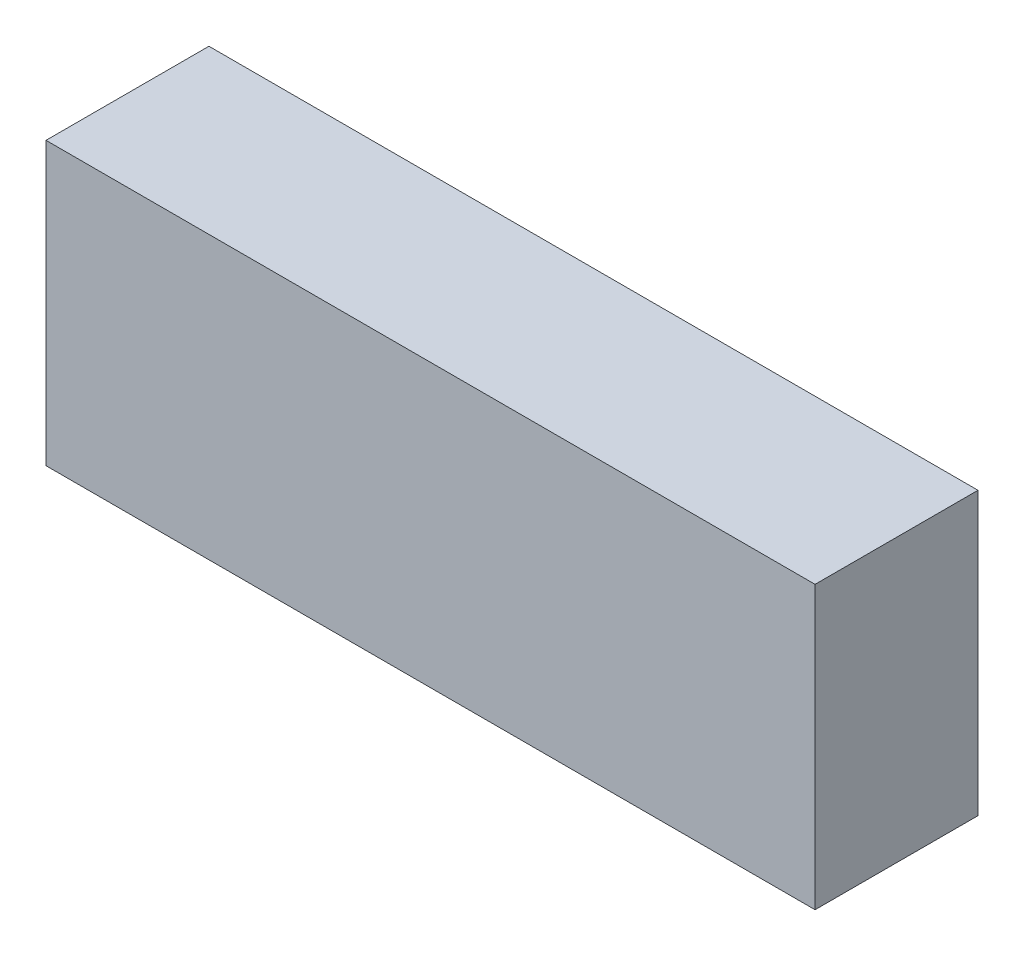
SolidWorks part; units mm, degrees
ref_plane "Front Plane" through (0, 0, 0) normal (0, 0, 1) x (1, 0, 0)
ref_plane "Top Plane" through (0, 0, 0) normal (0, 1, 0) x (1, 0, 0)
ref_plane "Right Plane" through (0, 0, 0) normal (1, 0, 0) x (0, 0, -1)
sketch "Sketch1" plane through (0, 0, 0) normal (0, 0, 1) x (1, 0, 0)
  line L0 (-79.2368, -17.43) -> (-44.6155, -17.43) construction
  line L1 (-79.0368, -17.63) -> (-44.8155, -17.63)
  line L2 (-79.0368, -17.63) -> (-79.0368, -30.17)
  line L3 (-79.0368, -30.17) -> (-44.8155, -30.17)
  line L4 (-44.8155, -17.63) -> (-44.8155, -30.17)
  line L5 (-44.6155, -17.43) -> (-44.6155, -30.37) construction
  line L6 (-44.6155, -30.37) -> (-79.2368, -30.37) construction
  line L7 (-79.2368, -17.43) -> (-79.2368, -30.37) construction
  dimension "D1" = 0.2
  dimension "D2" = 0.2
  dimension "D3" = 0.2
  dimension "D4" = 0.2
extrude "Boss-Extrude1" add sketch "Sketch1" along normal blind 7.25
shell "Shell1" thickness 0.5
equation "\"D2@Sketch1\"=\"D1@Sketch1\""
equation "\"D3@Sketch1\"=\"D1@Sketch1\""
equation "\"D4@Sketch1\"=\"D1@Sketch1\""
